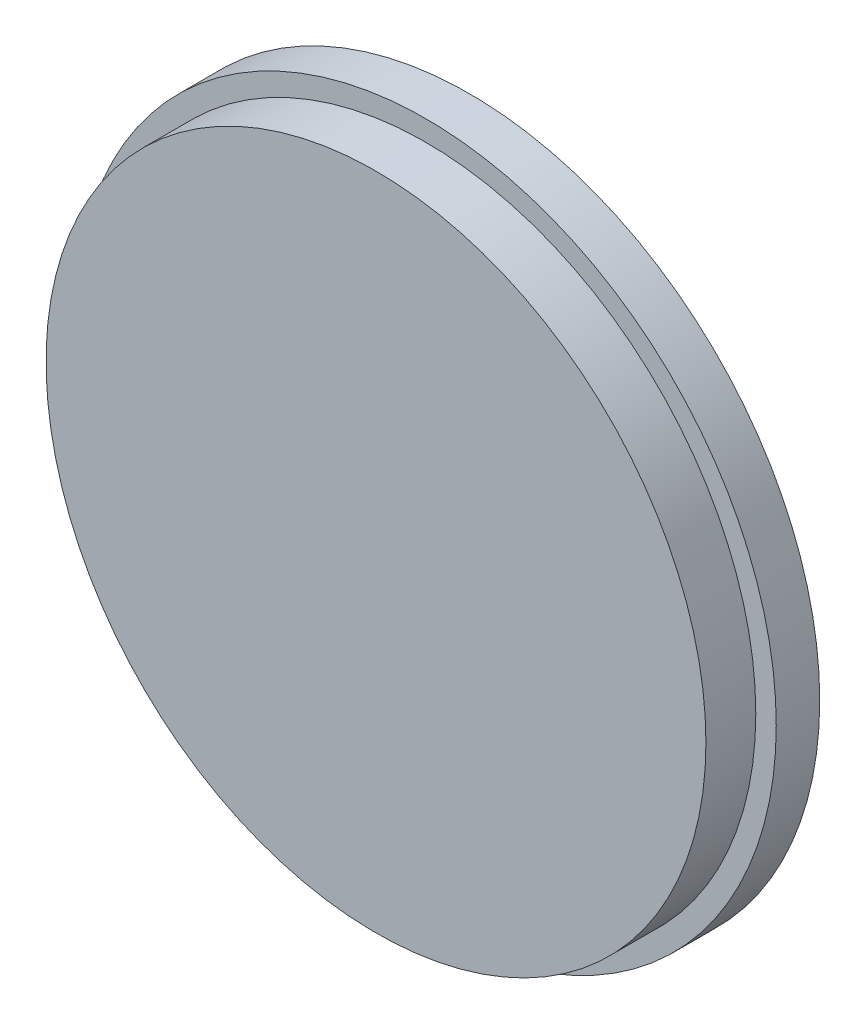
SolidWorks part; units mm, degrees
ref_plane "前视基准面" through (0, 0, 0) normal (0, 0, 1) x (1, 0, 0)
ref_plane "上视基准面" through (0, 0, 0) normal (0, 1, 0) x (1, 0, 0)
ref_plane "右视基准面" through (0, 0, 0) normal (1, 0, 0) x (0, 0, -1)
sketch "草图1" plane through (0, 0, 0) normal (0, 0, 1) x (1, 0, 0)
  circle A0 centre (0, 0) radius 25.8
  circle A1 centre (0, 0) radius 27.4
  dimension "D1" = 51.6
  dimension "D2" = 54.8
extrude "凸台-拉伸1" add sketch "草图1" against normal blind 3.4 contours A1
sketch "草图2" plane through (0, 0, 0) normal (0, 0, 1) x (1, 0, 0)
  circle A0 centre (0, 0) radius 25.8
  circle A1 centre (0, 0) radius 27.4
  dimension "D1" = 51.6
  dimension "D2" = 54.8
extrude "凸台-拉伸2" add sketch "草图2" along normal blind 3.9 contours A0
